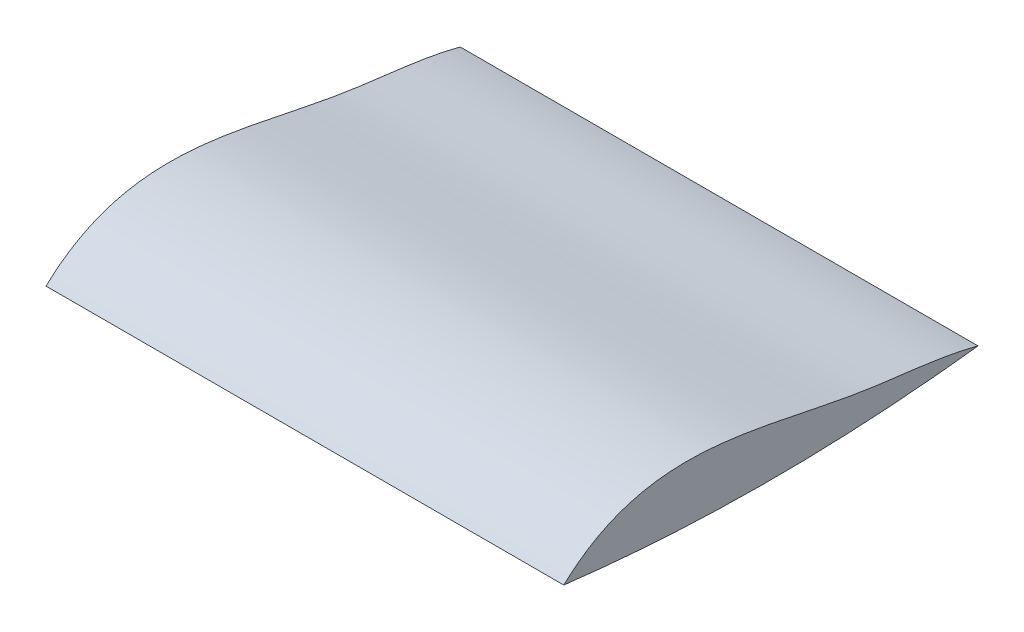
SolidWorks part; units mm, degrees
ref_plane "Front Plane" through (0, 0, 0) normal (0, 0, 1) x (1, 0, 0)
ref_plane "Top Plane" through (0, 0, 0) normal (0, 1, 0) x (1, 0, 0)
ref_plane "Right Plane" through (0, 0, 0) normal (1, 0, 0) x (0, 0, -1)
sketch "Sketch1" plane through (0, 0, 0) normal (1, 0, 0) x (0, 0, -1)
  spline S0 degree 3 poles (-43.701, -3.6751) (60.094, 93.5577) (246.6646, 18.2597) (417.6994, 8.7408) (464.299, -3.6751) knots 0 0 0 0 0.726777 1 1 1 1
  spline S1 degree 2 poles (-43.701, -3.6751) (209.423, -34.3264) (464.299, -3.6751) knots 0 0 0 1 1 1
  point P0 (-43.701, -3.6751)
  point P1 (464.299, -3.6751)
  dimension "D1" = 508
sketch "Sketch2" plane through (0, 0, 0) normal (0, 1, 0) x (1, 0, 0)
  line L0 (0, 45.5243) -> (-635, 45.5243)
  line L1 (0, -43.701) -> (0, 464.299) construction
  line L2 (0, 45.5243) -> (0, -13.3335) construction
  dimension "D1" = 635
  dimension "D2" = 90
sweep "Sweep1" add profiles "Sketch1" path "Sketch2"
sketch "Sketch3" plane through (-635, 0, 0) normal (-1, 0, 0) x (0, 0, 1)
  line L0 (-464.299, -3.6751) -> (43.701, -3.6751)
sketch "Sketch4" plane through (-635, 0, 0) normal (-1, 0, 0) x (0, 0, 1)
  line L0 (-464.299, -3.6751) -> (43.701, -3.6751)
